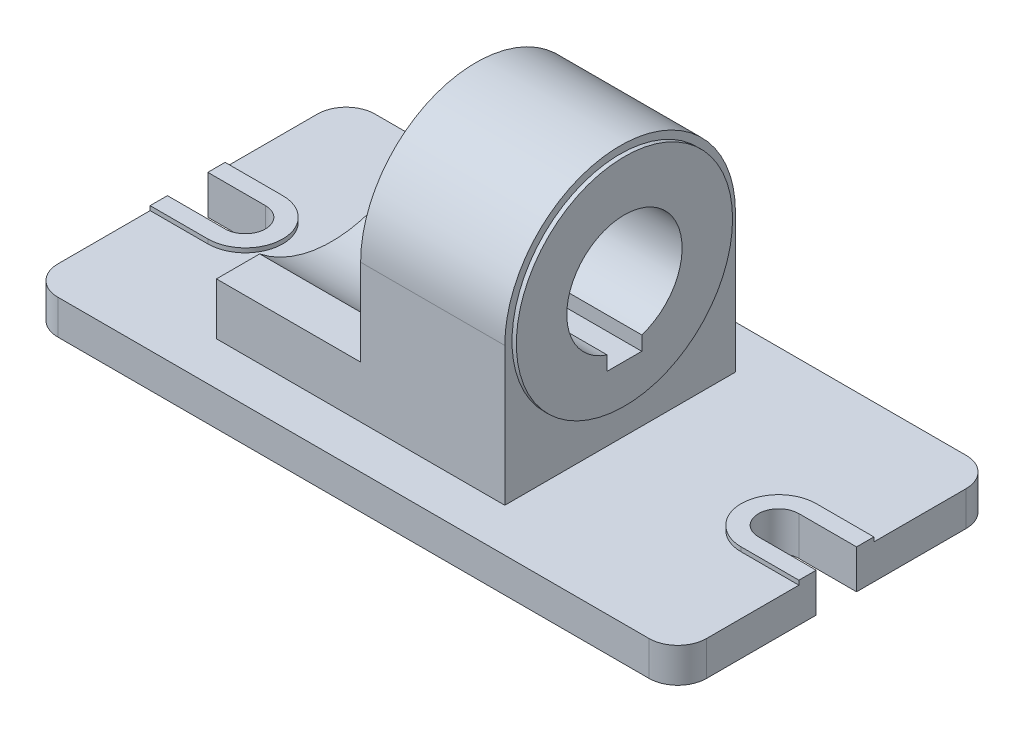
SolidWorks part; units mm, degrees
ref_plane "前视基准面" through (0, 0, 0) normal (0, 0, 1) x (1, 0, 0)
ref_plane "上视基准面" through (0, 0, 0) normal (0, 1, 0) x (1, 0, 0)
ref_plane "右视基准面" through (0, 0, 0) normal (1, 0, 0) x (0, 0, -1)
other "Configuration Table"
sketch "草图1" plane through (0, 0, 0) normal (0, 1, 0) x (1, 0, 0)
  line L0 (-132.5, 0) -> (-92.5, 0) construction
  line L1 (-102.5, -55) -> (102.5, -55)
  line L2 (-112.5, -45) -> (-112.5, 45)
  line L3 (-102.5, 55) -> (102.5, 55)
  line L4 (112.5, -45) -> (112.5, 45)
  line L5 (-112.5, -55) -> (112.5, 55) construction
  line L6 (-112.5, 55) -> (112.5, -55) construction
  line L7 (-132.5, 7) -> (-92.5, 7)
  line L8 (-132.5, -7) -> (-92.5, -7)
  line L9 (0, 0) -> (0, 39.0798) construction
  line L10 (132.5, 0) -> (92.5, 0) construction
  line L11 (132.5, 7) -> (92.5, 7)
  line L12 (132.5, -7) -> (92.5, -7)
  arc A0 (-102.5, -55) -> (-112.5, -45) centre (-102.5, -45) cw
  arc A1 (102.5, -55) -> (112.5, -45) centre (102.5, -45) ccw
  arc A2 (102.5, 55) -> (112.5, 45) centre (102.5, 45) cw
  arc A3 (-112.5, 45) -> (-102.5, 55) centre (-102.5, 45) cw
  arc A4 (-132.5, 7) -> (-132.5, -7) centre (-132.5, 0) ccw
  arc A5 (-92.5, -7) -> (-92.5, 7) centre (-92.5, 0) ccw
  arc A6 (132.5, 7) -> (132.5, -7) centre (132.5, 0) cw
  arc A7 (92.5, -7) -> (92.5, 7) centre (92.5, 0) cw
  point P0 (0, 0)
  point P20 (-112.5, 0)
  point P29 (112.5, 0)
  dimension "D3" = 10
  dimension "D4" = 7
  dimension "D1" = 110
  dimension "D2" = 225
  dimension "D5" = 185
extrude "凸台-拉伸1" add sketch "草图1" along normal mid plane 12 contours L12 A7 L11 L4 A2 L3 A3 L2 L7 A5 L8 A0 L1 A1
sketch "草图2" plane through (0, 6, 0) normal (0, 1, 0) x (1, 0, 0)
  line L0 (-132.5, 0) -> (-92.5, 0) construction
  line L1 (-132.5, 13) -> (-92.5, 13)
  line L2 (-132.5, -13) -> (-92.5, -13)
  line L4 (0, 0) -> (0, 39.0798) construction
  line L5 (0, 0) -> (0, 39.0798) construction
  line L6 (132.5, 0) -> (92.5, 0) construction
  line L7 (132.5, 13) -> (92.5, 13)
  line L8 (132.5, -13) -> (92.5, -13)
  line L9 (112.5, -45) -> (112.5, 45) construction
  line L10 (-112.5, -45) -> (-112.5, 45) construction
  line L11 (112.5, -13) -> (112.5, 13)
  line L12 (-112.5, -13) -> (-112.5, 13)
  line L13 (-132.5, -7) -> (-92.5, -7) construction
  line L14 (132.5, -7) -> (92.5, -7) construction
  line L15 (-112.5, -7) -> (-92.5, -7)
  line L16 (112.5, -7) -> (92.5, -7)
  line L17 (132.5, 7) -> (92.5, 7) construction
  line L18 (-132.5, 7) -> (-92.5, 7) construction
  line L39 (112.5, 7) -> (92.5, 7)
  line L40 (-112.5, 7) -> (-92.5, 7)
  arc A0 (-132.5, 13) -> (-132.5, -13) centre (-132.5, 0) ccw
  arc A1 (-92.5, -13) -> (-92.5, 13) centre (-92.5, 0) ccw
  arc A2 (132.5, 13) -> (132.5, -13) centre (132.5, 0) cw
  arc A3 (92.5, -13) -> (92.5, 13) centre (92.5, 0) cw
  arc A4 (92.5, 7) -> (92.5, -7) centre (92.5, 0) ccw construction
  arc A5 (-92.5, -7) -> (-92.5, 7) centre (-92.5, 0) ccw construction
  arc A6 (92.5, 7) -> (92.5, -7) centre (92.5, 0) ccw
  arc A7 (-92.5, -7) -> (-92.5, 7) centre (-92.5, 0) ccw
  point P2 (-112.5, 0)
  point P13 (112.5, 0)
  line M5 (112.5, -7) -> (92.5, -7)
  arc M6 (92.5, -7) -> (92.5, 7) centre (92.5, 0) cw
  line M7 (92.5, 7) -> (112.5, 7)
  line M8 (112.5, 7) -> (112.5, 45)
  line M12 (-112.5, 45) -> (-112.5, 7)
  line M13 (-112.5, 7) -> (-92.5, 7)
  arc M14 (-92.5, 7) -> (-92.5, -7) centre (-92.5, 0) cw
  line M15 (-92.5, -7) -> (-112.5, -7)
  line M16 (-112.5, -7) -> (-112.5, -45)
  line M20 (112.5, -45) -> (112.5, -7)
  dimension "D1" = 13
extrude "凸台-拉伸2" add sketch "草图2" along normal mid plane 3 contours L2 A1 L1 M12 M13 M14 M15 M16 | A3 L8 L7 M20 M5 M6 M7 M8
sketch "草图3" plane through (112.5, 0, 0) normal (1, 0, 0) x (0, 0, -1)
  line L0 (-45, 6) -> (-13, 6) construction
  line L1 (-40, 6) -> (40, 6)
  line L2 (-40, 6) -> (-40, 54)
  line L3 (-40, 54) -> (40, 54) construction
  line L4 (40, 6) -> (40, 54)
  line L5 (0, 0) -> (0, 39.6835) construction
  line L6 (7, -6) -> (45, -6) construction
  arc A0 (40, 54) -> (-40, 54) centre (0, 54) ccw
  dimension "D1" = 80
  dimension "D2" = 60
extrude "凸台-拉伸3" add sketch "草图3" along normal mid plane 50 from offset 100 offset against normal yes
sketch "草图4" plane through (37.5, 0, 0) normal (1, 0, 0) x (0, 0, -1)
  arc A0 (40, 54) -> (-40, 54) centre (0, 54) ccw construction
  arc A1 (40, 54) -> (-40, 54) centre (0, 54) ccw construction
  circle A2 centre (0, 54) radius 37.5
  dimension "D1" = 75
extrude "凸台-拉伸4" add sketch "草图4" along normal mid plane 3
sketch "草图5" plane through (39, 0, 0) normal (1, 0, 0) x (0, 0, -1)
  line L1 (-6, 30) -> (6, 30)
  line L2 (-6, 30) -> (-6, 38)
  line L3 (-6, 38) -> (6, 38)
  line L4 (6, 30) -> (6, 38)
  line L5 (-6, 30) -> (6, 38) construction
  line L6 (-6, 38) -> (6, 30) construction
  circle A0 centre (0, 54) radius 20
  circle A1 centre (0, 54) radius 37.5
  circle A2 centre (0, 54) radius 37.5 construction
  point P1 (0, 34)
  point P9 (0, 74)
  dimension "D2" = 40
  dimension "D3" = 12
  dimension "D4" = 44
  dimension "D1" = 0
extrude "切除-拉伸1" cut sketch "草图5" against normal through all contours A0 | L1 L4 L3 L2
sketch "草图6" plane through (0, 6, 0) normal (0, 1, 0) x (1, 0, 0)
  line L0 (-12.5, 40) -> (-12.5, -40) construction
  line L1 (-12.5, 0) -> (-62.5, 0) construction
  line L2 (-12.5, -40) -> (-12.5, 40)
  line L3 (-12.5, 40) -> (-62.5, 40)
  line L4 (-62.5, -40) -> (-62.5, 40)
  line L5 (-12.5, -40) -> (-62.5, -40)
  line L6 (-12.5, -40) -> (-12.5, 40) construction
  dimension "D1" = 50
extrude "凸台-拉伸5" add sketch "草图6" along normal mid plane 3
sketch "草图7" plane through (-12.5, 0, 0) normal (-1, 0, 0) x (0, 0, 1)
  line L0 (0, 0) -> (0, 48.516) construction
  line L1 (-40, 7.5) -> (-25, 7.5)
  line L2 (-40, 7.5) -> (-40, 24)
  line L3 (-40, 24) -> (-25, 24)
  line L4 (-25, 7.5) -> (-25, 24)
  line L5 (40, 24) -> (25, 24)
  line L6 (25, 7.5) -> (25, 24)
  line L7 (40, 7.5) -> (25, 7.5)
  line L8 (40, 7.5) -> (40, 24)
  arc A0 (-25, 24) -> (25, 24) centre (0, 55.225) ccw
  arc A1 (6, 34.9212) -> (-6, 34.9212) centre (0, 54) ccw construction
  arc A2 (6, 34.9212) -> (-6, 34.9212) centre (0, 54) ccw construction
  point P13 (0, 0)
  line M11 (-40, 54) -> (-40, 7.5)
  line M12 (-40, 7.5) -> (40, 7.5)
  line M13 (40, 7.5) -> (40, 54)
  dimension "D1" = 40
  dimension "D2" = 30
  dimension "D3" = 15
extrude "凸台-拉伸6" add sketch "草图7" along normal up to vertex (50 mm away) contours A0 L4 L6 M12 | L4 L3 M12 M11 | L6 L5 M12 M13 up to point (-62.5, 7.5, -40)
